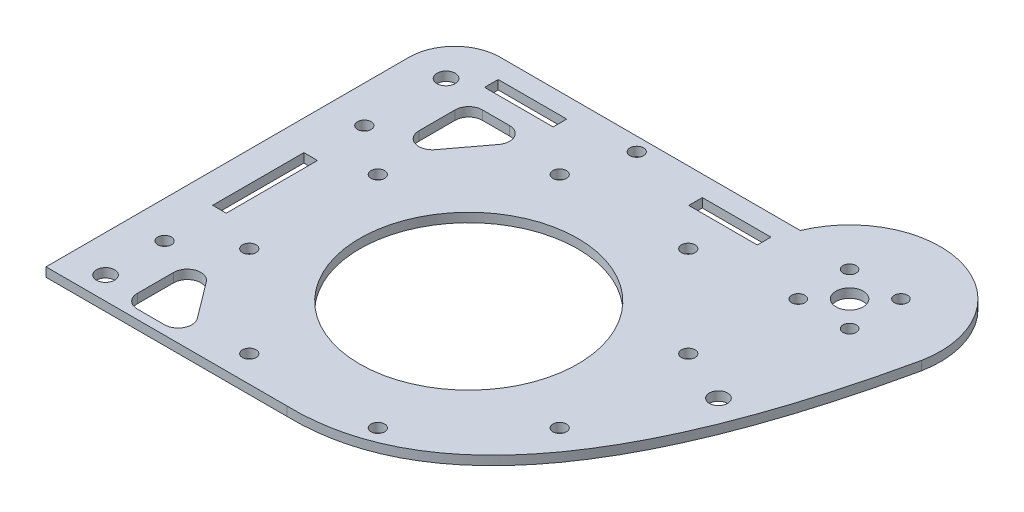
SolidWorks part; units mm, degrees
material "Thornel Mat VMA"
ref_plane "前视基准面" through (0, 0, 0) normal (0, 0, 1) x (1, 0, 0)
ref_plane "上视基准面" through (0, 0, 0) normal (0, 1, 0) x (1, 0, 0)
ref_plane "右视基准面" through (0, 0, 0) normal (1, 0, 0) x (0, 0, -1)
other "Configuration Table"
sketch "草图1" plane through (0, 0, 0) normal (0, 1, 0) x (1, 0, 0)
  line L1 (0, -40) -> (-53.1155, -40)
  line L49 (-39.0451, 42.5334) -> (-39.0451, 45.5334)
  line L55 (21.0549, 42.5) -> (5.9549, 42.5)
  line L56 (-23.9451, 42.5334) -> (-23.9451, 45.5334)
  line L57 (-23.9451, 42.5334) -> (-39.0451, 45.5334) construction
  line L58 (-23.9451, 45.5334) -> (-39.0451, 45.5334)
  line L59 (-23.9451, 42.5334) -> (-39.0451, 42.5334)
  line L60 (-23.9451, 45.5334) -> (-39.0451, 42.5334) construction
  line L61 (5.9549, 42.5) -> (5.9549, 45.5)
  line L64 (21.0549, 45.5) -> (5.9549, 45.5)
  line L65 (-43.5, -9.915) -> (-46.5, -9.915)
  line L66 (-43.5, -9.915) -> (-43.5, 10.185)
  line L67 (-43.5, 10.185) -> (-46.5, 10.185)
  line L68 (-46.5, -9.915) -> (-46.5, 10.185)
  line L69 (21.0549, 42.5) -> (21.0549, 45.5)
  line L73 (-38, 38) -> (-38, 18)
  line L74 (-38, 38) -> (-23, 38)
  line L75 (-38, 18) -> (-23, 38)
  line L76 (0, 0) -> (-75.4627, 0) construction
  line L77 (-38, -38) -> (-38, -18)
  line L78 (-38, -38) -> (-23, -38)
  line L79 (-38, -18) -> (-23, -38)
  line L80 (-53.1155, -40) -> (-53.1155, 50)
  line L81 (-53.1155, 50) -> (23.0351, 50)
  circle A1 centre (0, 0) radius 24
  circle A2 centre (41.5198, 42.3635) radius 3
  circle A3 centre (0, 0) radius 40 construction
  circle A8 centre (46, 9) radius 2
  circle A9 centre (46, 9) radius 5 construction
  circle A12 centre (-45, 40) radius 5 construction
  circle A13 centre (-45, 40) radius 2
  circle A14 centre (-45, -35) radius 2
  circle A15 centre (-45, -35) radius 4.3381 construction
  circle A16 centre (35.8629, 48.0204) radius 1.45
  circle A17 centre (47.1767, 48.0204) radius 1.45
  circle A18 centre (47.1767, 36.7067) radius 1.45
  circle A19 centre (35.8629, 36.7067) radius 1.45
  circle A20 centre (-45, 22) radius 1.5
  circle A29 centre (-45, -22) radius 1.5
  circle A30 centre (0, 0) radius 37 construction
  circle A32 centre (34.1835, 14.1593) radius 1.5
  circle A33 centre (34.1835, -14.1593) radius 1.5
  circle A34 centre (14.1593, -34.1835) radius 1.5
  circle A35 centre (-14.1593, -34.1835) radius 1.5
  circle A36 centre (-34.1835, -14.1593) radius 1.5
  circle A37 centre (-34.1835, 14.1593) radius 1.5
  circle A38 centre (-14.1593, 34.1835) radius 1.5
  circle A39 centre (14.1593, 34.1835) radius 1.5
  arc A41 (61.1528, 38.5497) -> (23.0351, 50) centre (41.5198, 42.3635) ccw
  circle A42 centre (-10, 47) radius 1.5
  spline S0 degree 2 poles (61.1528, 38.5497) (43.7678, -41.0443) (0, -40) knots 0 0 0 0.762442 0.762442 0.762442
  point P0 (0, 0)
  point P12 (0, 0)
  point P13 (0, 0)
  point P26 (0, 0)
  point P44 (41.5198, 42.3635)
  point P54 (0, 0)
  point P61 (0, 0)
  dimension "D1" = 8
  dimension "D2" = 4
extrude "凸台-拉伸1" add sketch "草图1" along normal blind 2
fillet "圆角1" radius 10 1 edges at (-53.1155, 1, -50)
fillet "圆角2" radius 3 6 edges at (-38, 1, 38) (-23, 1, 38) (-38, 1, 18) (-38, 1, -18) (-23, 1, -38) (-38, 1, -38)
